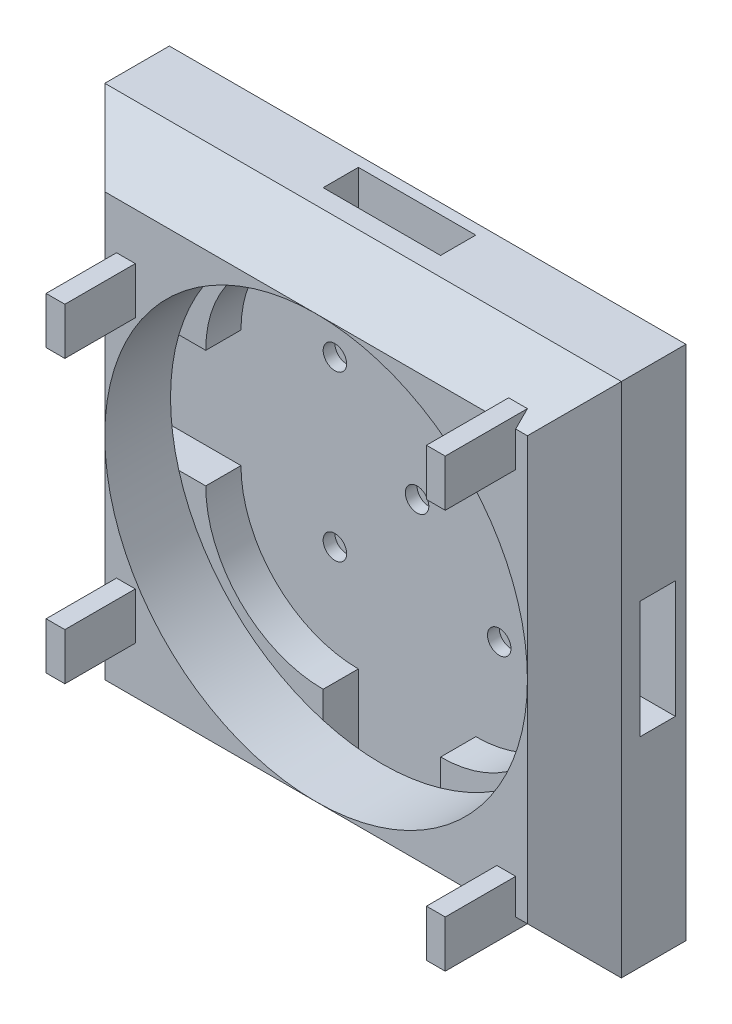
SolidWorks part; units mm, degrees
material "3.0205 (EN-AW 1200)"
ref_plane "정면" through (0, 0, 0) normal (0, 0, 1) x (1, 0, 0)
ref_plane "윗면" through (0, 0, 0) normal (0, 1, 0) x (1, 0, 0)
ref_plane "우측면" through (0, 0, 0) normal (1, 0, 0) x (0, 0, -1)
sketch "스케치1" plane through (0, 0, 0) normal (0, 0, 1) x (1, 0, 0)
  line L1 (-110, 110) -> (110, 110)
  line L2 (-110, 110) -> (-110, -110)
  line L3 (-110, -110) -> (110, -110)
  line L4 (110, 110) -> (110, -110)
  line L5 (-110, 110) -> (110, -110) construction
  line L6 (-110, -110) -> (110, 110) construction
  point P0 (0, 0)
  dimension "D1" = 220
  dimension "D2" = 220
extrude "보스-돌출1" add sketch "스케치1" along normal blind 20 draft 45
sketch "스케치2" plane through (0, 0, 20) normal (0, 0, 1) x (1, 0, 0)
  line L0 (90, 90) -> (-90, 90) construction
  line L1 (-85, 70) -> (-77, 70)
  line L2 (-85, 70) -> (-85, 50)
  line L3 (-85, 50) -> (-77, 50)
  line L4 (-77, 70) -> (-77, 50)
  line L5 (-90, -90) -> (90, -90) construction
  line L6 (-90, 90) -> (-90, -90) construction
  line L11 (44, 0) -> (-44, 0) construction
  line L16 (-77, -70) -> (-77, -50)
  line L17 (-85, -50) -> (-77, -50)
  line L18 (-85, -70) -> (-85, -50)
  line L19 (-85, -70) -> (-77, -70)
  line L21 (77, 95) -> (85, 95)
  line L22 (77, 95) -> (77, 75)
  line L23 (77, 75) -> (85, 75)
  line L24 (85, 95) -> (85, 75)
  line L25 (77, -75) -> (85, -75)
  line L26 (77, -75) -> (77, -95)
  line L27 (77, -95) -> (85, -95)
  line L28 (85, -75) -> (85, -95)
  line L32 (90, -90) -> (90, 90) construction
  dimension "D1" = 8
  dimension "D2" = 20
  dimension "D3" = 20
  dimension "D4" = 13
  dimension "D5" = 5
  dimension "D6" = 20
  dimension "D7" = 20
  dimension "D8" = 5
  dimension "D9" = 8
  dimension "D10" = 8
  dimension "D11" = 13
  dimension "D12" = 13
extrude "보스-돌출2" add sketch "스케치2" along normal blind 30 and the other way up to surface other way up to face at (0, 0, 0)
sketch "스케치3" plane through (0, 0, 20) normal (0, 0, 1) x (1, 0, 0)
  text T0 "WAYUP\r\n" font "Century Gothic" height 20
sketch "스케치4" plane through (0, 0, 0) normal (0, 0, -1) x (-1, 0, 0)
  line L1 (-110, 110) -> (110, 110)
  line L2 (-110, 110) -> (-110, -110)
  line L3 (-110, -110) -> (110, -110)
  line L4 (110, 110) -> (110, -110)
extrude "보스-돌출3" add sketch "스케치4" along normal blind 30
ref_plane "평면1" through (0, 0, -23) normal (0, 0, -1) x (-1, 0, 0)
sketch "스케치6" plane through (0, 0, -23) normal (0, 0, -1) x (-1, 0, 0)
  line L0 (-110, 25) -> (-75, 25)
  line L1 (-110, 110) -> (-110, -110) construction
  line L2 (25, 110) -> (25, 75)
  line L3 (110, -25) -> (75, -25)
  line L4 (-25, -110) -> (-25, -75)
  line L5 (-75, -25) -> (-110, -25)
  line L6 (-110, -25) -> (-110, 25)
  line L7 (25, -75) -> (25, -110)
  line L8 (-110, -110) -> (110, -110) construction
  line L9 (25, -110) -> (-25, -110)
  line L10 (110, -25) -> (110, 25)
  line L11 (110, -110) -> (110, 110) construction
  line L12 (110, 25) -> (75, 25)
  line L13 (25, 110) -> (-25, 110)
  line L14 (110, 110) -> (-110, 110) construction
  line L15 (-25, 110) -> (-25, 75)
  arc A0 (-75, 25) -> (-25, 75) centre (-25, 25) cw
  arc A1 (25, 75) -> (75, 25) centre (25, 25) cw
  arc A2 (75, -25) -> (25, -75) centre (25, -25) cw
  arc A3 (-25, -75) -> (-75, -25) centre (-25, -25) cw
  point P21 (0, 0)
  dimension "D3" = 50
  dimension "D2" = 50
  dimension "D4" = 0
  dimension "D1" = 4
extrude "컷-돌출1" cut sketch "스케치6" against normal blind 15
sketch "스케치7" plane through (0, 0, 20) normal (0, 0, 1) x (1, 0, 0)
  circle A0 centre (0, 0) radius 90
  dimension "D1" = 180
extrude "컷-돌출2" cut sketch "스케치7" against normal blind 28
sketch "스케치9" plane through (0, 0, -23) normal (0, 0, 1) x (1, 0, 0)
  line L4 (44, 0) -> (-44, 0) construction
  circle A0 centre (-35, 35) radius 5
  circle A1 centre (0, 0) radius 5
  circle A2 centre (35, 35) radius 5
  circle A5 centre (-35, -35) radius 5 [skipped]
  circle A6 centre (35, -35) radius 5 [skipped]
  circle A7 centre (35, -35) radius 5
  circle A8 centre (-35, -35) radius 5
  point P15 (0, 0)
  dimension "D1" = 10
  dimension "D7" = 10
  dimension "D2" = 40
  dimension "D3" = 40
  dimension "D5" = 40
  dimension "D6" = 40
  dimension "D4" = 4
extrude "컷-돌출3" cut sketch "스케치9" against normal blind 5
sketch "스케치10" plane through (0, 110, 0) normal (0, 1, 0) x (1, 0, 0)
  line L0 (-110, 30) -> (-110, 27.5)
  line L1 (-110, 30) -> (-110, 0) construction
  line L2 (-110, 27.5) -> (-107.5, 30)
  line L3 (-110, 30) -> (110, 30) construction
  line L4 (-107.5, 30) -> (-110, 30)
  dimension "D1" = 2.5
  dimension "D2" = 2.5
extrude "컷-돌출4" cut sketch "스케치10" against normal through all
sketch "스케치11" plane through (0, 0, 0) normal (0, 1, 0) x (1, 0, 0)
  line L0 (0, -68.4326) -> (0, 99.1854) construction
pattern_circular "원형 패턴2" count 4 over 360 about axis through (0, 0, 0) along (0, 0, 1) of "컷-돌출4"
